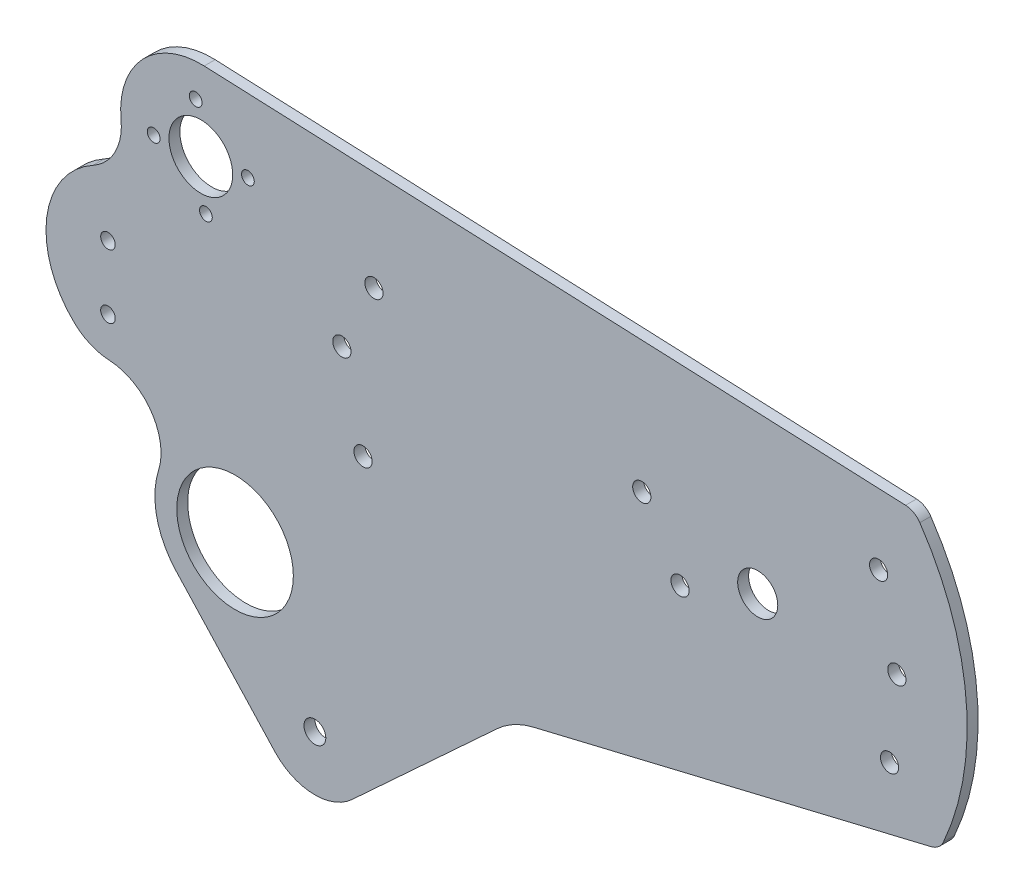
SolidWorks part; units mm, degrees
ref_plane "Front Plane" through (0, 0, 0) normal (0, 0, 1) x (1, 0, 0)
ref_plane "Top Plane" through (0, 0, 0) normal (0, 1, 0) x (1, 0, 0)
ref_plane "Right Plane" through (0, 0, 0) normal (1, 0, 0) x (0, 0, -1)
sketch "Sketch1" plane through (0, 0, 0) normal (0, 0, 1) x (1, 0, 0)
  line L0 (86.8854, -33.5) -> (-137.2004, -33.5) construction
  line L1 (-111.886, 49.4802) -> (80.595, 41.3179)
  line L2 (-115.2069, 49.6211) -> (-101.035, -81.6153) construction
  line L3 (-97.8208, -80.7688) -> (92.1699, -30.731) construction
  line L4 (78.7977, 41.3942) -> (86.7407, -32.1609) construction
  line L5 (-108.121, -15.9971) -> (82.7692, 4.6166) construction
  line L6 (91, -33.5) -> (-88.5, -33.5) construction
  line L7 (-97.4673, 5.5) -> (-155.3054, 5.5) construction
  line L8 (-138.3, -14) -> (-155.3054, -14) construction
  line L9 (-138.3, 5.5) -> (-138.3, -33.5) construction
  line L10 (-155.3054, 5.5) -> (-155.3054, -33.5) construction
  line L11 (40.0178, 33.5) -> (40.0178, -33.5) construction
  line L12 (-101.0425, -81.5467) -> (-98.2952, -80.8881)
  line L13 (-91.5, 33.5) -> (88, 33.5) construction
  line L14 (-68.3, -21.5) -> (-107.0746, -25.6872) construction
  line L16 (-98.2952, -80.8881) -> (-90.8208, -79.0963)
  line L17 (-119.5948, -74.4106) -> (-92.5405, -103.7404)
  line L18 (-71.3446, -104.5958) -> (-31.4414, -67.7885)
  line L19 (-138.3, -5.25) -> (-81.5148, -93.5701) construction
  line L20 (-21.4819, -62.4739) -> (87.5999, -36.3241)
  circle A0 centre (40.0178, 0) radius 5.5
  circle A1 centre (-112.8181, 27.5) radius 13 construction
  circle A2 centre (-103.4238, -59.4942) radius 13 construction
  arc A3 (-91.5, 33.5) -> (-88.5, -33.5) centre (-18.0922, 3.2198) ccw construction
  circle A4 centre (-68.3, -21.5) radius 2.5
  circle A5 centre (-68.3, -21.5) radius 2.5 construction
  circle A6 centre (-138.3, -5.25) radius 2
  circle A7 centre (-138.3, -22.75) radius 2
  arc A8 (-142.3827, 10.6321) -> (-147.5429, -29.3643) centre (-130.3054, -11.2571) ccw
  arc A9 (-147.5429, -29.3643) -> (-137.2004, -33.5) centre (-137.2004, -18.5) ccw
  circle A10 centre (-112.8181, 27.5) radius 22
  arc A11 (87.5999, -36.3241) -> (91, -33.5) centre (86.4343, -31.4619) ccw
  circle A12 centre (-103.4238, -59.4942) radius 22
  arc A13 (91, -33.5) -> (84.5157, 39.1371) centre (22.6589, -2.9929) ccw
  arc A14 (91, -33.5) -> (88, 33.5) centre (22.6589, -2.9929) ccw construction
  arc A15 (84.5157, 39.1371) -> (80.595, 41.3179) centre (80.3831, 36.3224) ccw
  arc A17 (-124.4228, -52.9336) -> (-137.9704, -33.4802) centre (-138.7403, -48.4604) ccw
  arc A18 (-142.3827, 10.6321) -> (-134.7058, 25.2795) centre (-149.6292, 23.7656) ccw
  circle A19 centre (-74.1, 1.7) radius 2.5
  circle A20 centre (-65.3, 20) radius 2.5
  circle A21 centre (8.2, 8.3) radius 2.5
  circle A23 centre (18.7, -8.7) radius 2.5
  circle A25 centre (78.2, -0.1) radius 2.5
  circle A26 centre (76.2, -22) radius 2.5
  circle A27 centre (73.2, 22.3) radius 2.5
  circle A28 centre (73.2, 22.3) radius 2.5 construction
  circle A29 centre (78.2, -0.1) radius 2.5 construction
  circle A31 centre (8.2, 8.3) radius 2.5 construction
  circle A32 centre (18.7, -8.7) radius 2.5 construction
  circle A33 centre (76.2, -22) radius 2.5 construction
  circle A34 centre (-74.1, 1.7) radius 2.5 construction
  circle A35 centre (-65.3, 20) radius 2.5 construction
  circle A36 centre (-114.2138, 40.4249) radius 1.75
  circle A37 centre (-99.8933, 28.8957) radius 1.75
  circle A38 centre (-111.4224, 14.5751) radius 1.75
  circle A39 centre (-125.743, 26.1043) radius 1.75
  circle A40 centre (-104.8196, -46.5694) radius 1.75
  circle A41 centre (-90.499, -58.0985) radius 1.75
  circle A42 centre (-102.0281, -72.4191) radius 1.75
  circle A43 centre (-116.3487, -60.89) radius 1.75
  circle A44 centre (40.0178, 0) radius 35 construction
  circle A45 centre (40.0178, 0) radius 43
  circle A49 centre (-103.4238, -59.4942) radius 16
  circle A50 centre (-112.8181, 27.5) radius 16 construction
  circle A51 centre (-112.8181, 27.5) radius 8.75
  circle A52 centre (-103.4238, -59.4942) radius 8.75
  arc A53 (91, -33.5) -> (88, 33.5) centre (22.6589, -2.9929) ccw construction
  arc A56 (-92.5405, -103.7404) -> (-71.3446, -104.5958) centre (-81.5148, -93.5701) ccw
  circle A57 centre (-81.5148, -93.5701) radius 3
  arc A59 (-21.4819, -62.4739) -> (-31.4414, -67.7885) centre (-16.2632, -84.2433) ccw
  point P52 (82.7692, 4.6166)
  point P109 (-112.8181, 27.5)
  point P118 (-103.4238, -59.4942)
  point P135 (-21.7216, -74.0142)
  dimension "D5" = 4
  dimension "D6" = 25
  dimension "D9" = 15
  dimension "D13" = 10
  dimension "D14" = 26
  dimension "D11" = 44
  dimension "D15" = 3.5
  dimension "D12" = 70
  dimension "D19" = 11
  dimension "D20" = 17.5
  dimension "D22" = 32
  dimension "D24" = 105
  dimension "D25" = 6
  dimension "D2" = 39
  dimension "D3" = 70
  dimension "D4" = 17.5
  dimension "D7" = 14
  dimension "D8" = 10
  dimension "D10" = 87.5
  dimension "D21" = 192
  dimension "D23" = 39
  dimension "D18" = 8
  dimension "D16" = 4
  dimension "D17" = 4
extrude "Boss-Extrude1" add sketch "Sketch1" along normal blind 3
